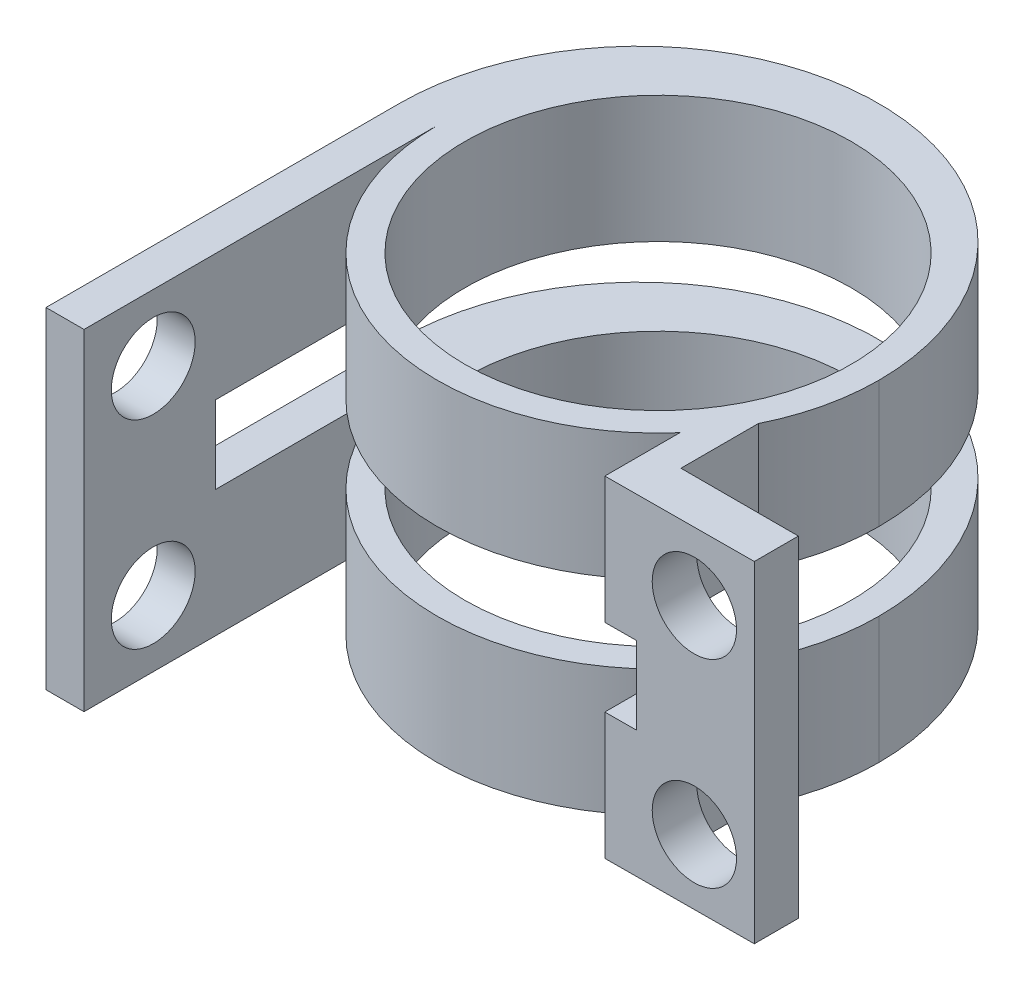
SolidWorks part; units mm, degrees
ref_plane "Front Plane" through (0, 0, 0) normal (0, 0, 1) x (1, 0, 0)
ref_plane "Top Plane" through (0, 0, 0) normal (0, 1, 0) x (1, 0, 0)
ref_plane "Right Plane" through (0, 0, 0) normal (1, 0, 0) x (0, 0, -1)
sketch "Sketch1" plane through (0, 0, 0) normal (0, 1, 0) x (1, 0, 0)
  line L3 (7.55, -9.9616) -> (14.2891, -9.9272)
  line L7 (-10, 0) -> (-10, -16.0059)
  line L9 (-9.9489, -10.0509) -> (11.2022, -9.943) construction
  line L12 (11.2022, -9.943) -> (15.0508, -9.9234) construction
  line L13 (14.2891, -9.9272) -> (14.2891, -7.931)
  line L16 (-10, -16.0059) -> (-11.7226, -16.0059)
  line L17 (-11.7226, -16.0059) -> (-11.7226, 0)
  line L20 (7.55, -6.5572) -> (7.55, -9.9616)
  line L21 (14.2891, -7.931) -> (8.9677, -7.931)
  line L22 (8.9677, -7.931) -> (8.9677, 0)
  arc A5 (-10, 0) -> (7.55, -6.5572) centre (0, 0) ccw
  circle A6 centre (0, 0) radius 10
  circle A7 centre (0, 0) radius 9
  arc A8 (-11.7226, 0) -> (10, 0) centre (-0.8613, 0) cw
  circle A10 centre (0, 0) radius 8.75
extrude "Boss-Extrude1" add sketch "Sketch1" against normal blind 15
sketch "Sketch2" plane through (-10.8239, 0, 0) normal (-1, 0, 0) x (0, 0, 1)
  line L0 (16.0059, -15) -> (0, -15) construction
  line L1 (16.0059, 0) -> (0, 0) construction
  circle A0 centre (12.8705, -12) radius 1.9
  circle A1 centre (12.8705, -3) radius 1.9
  point P2 (0, 0)
  point P5 (0, 0)
  dimension "D1" = 3
  dimension "D2" = 3
extrude "Cut-Extrude1" cut sketch "Sketch2" along normal mid plane 40
sketch "Sketch3" plane through (0, 0, 7.931) normal (0, 0, -1) x (-1, 0, 0)
  circle A0 centre (-11.5866, -12.0514) radius 1.9
  circle A1 centre (-11.5866, -3.0719) radius 1.9
  point P4 (0, 0)
extrude "Cut-Extrude2" cut sketch "Sketch3" against normal blind 10 contours A1 | A0
sketch "Sketch4" plane through (8.9677, 0, 0) normal (1, 0, 0) x (0, 0, -1)
  line L2 (-10.048, -5.7413) -> (-10.048, -9.2587)
  line L12 (-10.048, -5.7413) -> (20.1755, -5.7413)
  line L13 (-10.048, -5.7413) -> (-10.048, -9.2587)
  line L14 (-10.048, -9.2587) -> (20.1755, -9.2587)
  line L15 (20.1755, -5.7413) -> (20.1755, -9.2587)
  line M6 (-7.931, 0) -> (-7.931, -15)
  line M12 (-4.425, -15) -> (-4.425, 0)
extrude "Cut-Extrude3" cut sketch "Sketch4" against normal blind 129 contours L15 L12 L14 M12 | L14 L12 M6 M12 | L2 L14 L12 M6
sketch "Sketch5" plane through (-10, 0, 0) normal (1, 0, 0) x (0, 0, -1)
  line L0 (-7.931, -5.7413) -> (-4.425, -5.7413) construction
  line L1 (-6.178, -5.7413) -> (8.75, -5.7413)
  line L2 (-6.178, -5.7413) -> (-6.178, -9.2587)
  line L3 (-6.178, -9.2587) -> (8.75, -9.2587)
  line L4 (8.75, -5.7413) -> (8.75, -9.2587)
extrude "Cut-Extrude4" cut sketch "Sketch5" against normal mid plane 79
